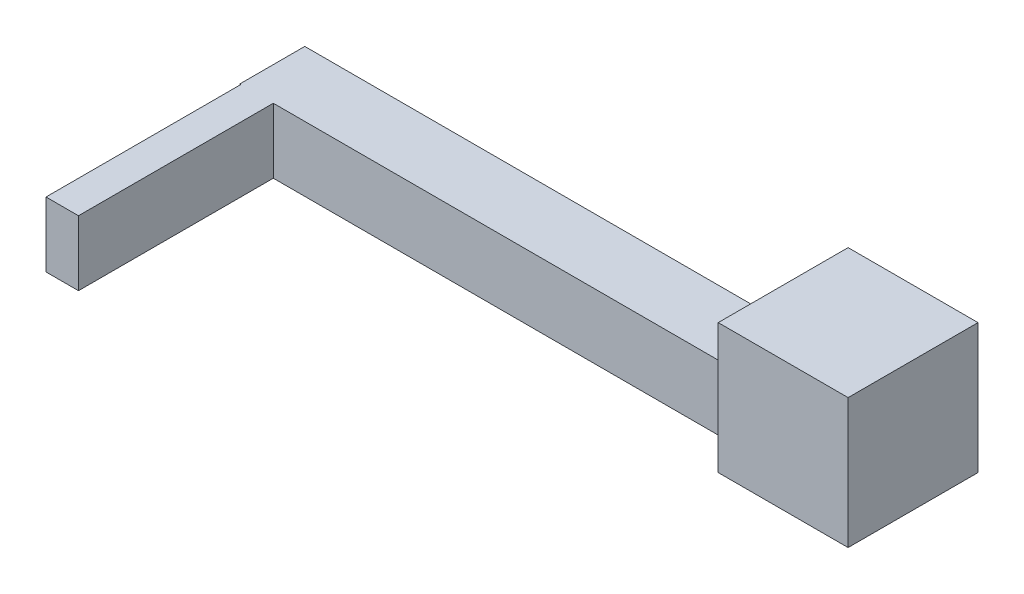
SolidWorks part; units mm, degrees
ref_plane "Front Plane" through (0, 0, 0) normal (0, 0, 1) x (1, 0, 0)
ref_plane "Top Plane" through (0, 0, 0) normal (0, 1, 0) x (1, 0, 0)
ref_plane "Right Plane" through (0, 0, 0) normal (1, 0, 0) x (0, 0, -1)
sketch "Sketch1" plane through (0, 0, 0) normal (0, 1, 0) x (1, 0, 0)
  line L1 (40, -5) -> (-40, -5)
  line L2 (40, -5) -> (40, 5)
  line L3 (40, 5) -> (-40, 5)
  line L4 (-40, -5) -> (-40, 5)
  line L5 (40, -5) -> (-40, 5) construction
  line L6 (40, 5) -> (-40, -5) construction
  point P0 (0, 0)
  dimension "D1" = 80
  dimension "D2" = 10
sketch "Sketch3" plane through (0, 0, 0) normal (0, 1, 0) x (1, 0, 0)
  line L1 (58.6544, -10) -> (38.6544, -10)
  line L2 (58.6544, -10) -> (58.6544, 10)
  line L3 (58.6544, 10) -> (38.6544, 10)
  line L4 (38.6544, -10) -> (38.6544, 10)
  line L5 (58.6544, -10) -> (38.6544, 10) construction
  line L6 (58.6544, 10) -> (38.6544, -10) construction
  point P0 (48.6544, 0)
  dimension "D1" = 20
  dimension "D2" = 20
extrude "Boss-Extrude2" add sketch "Sketch3" along normal blind 20
extrude "Boss-Extrude3" add sketch "Sketch1" along normal blind 10
sketch "Sketch6" plane through (0, 0, 0) normal (0, 1, 0) x (1, 0, 0)
  line L0 (-40, -5) -> (38.6544, -5) construction
  line L1 (-34.8452, -35) -> (-39.8452, -35)
  line L2 (-34.8452, -35) -> (-34.8452, -5)
  line L3 (-34.8452, -5) -> (-39.8452, -5)
  line L4 (-39.8452, -35) -> (-39.8452, -5)
  line L5 (-34.8452, -35) -> (-39.8452, -5) construction
  line L6 (-34.8452, -5) -> (-39.8452, -35) construction
  point P0 (-37.3452, -20)
  dimension "D1" = 5
  dimension "D2" = 30
extrude "Boss-Extrude4" add sketch "Sketch6" along normal blind 10
